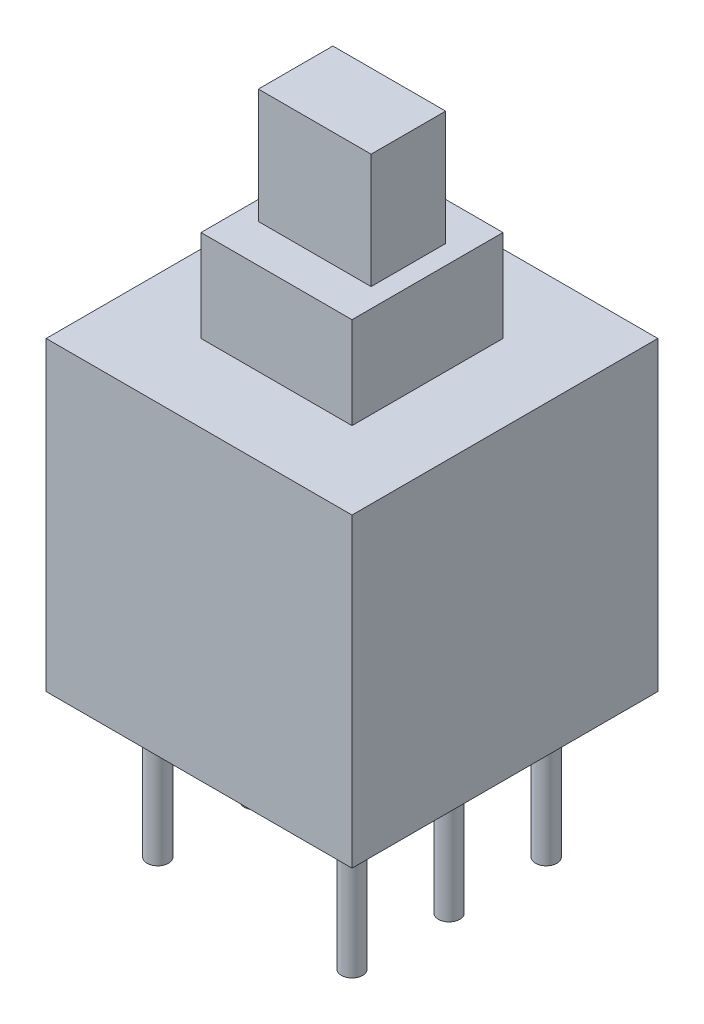
SolidWorks part; units mm, degrees
ref_plane "Front Plane" through (0, 0, 0) normal (0, 0, 1) x (1, 0, 0)
ref_plane "Top Plane" through (0, 0, 0) normal (0, 1, 0) x (1, 0, 0)
ref_plane "Right Plane" through (0, 0, 0) normal (1, 0, 0) x (0, 0, -1)
sketch "Sketch1" plane through (0, 0, 0) normal (0, 1, 0) x (1, 0, 0)
  line L1 (-4, -4) -> (4, -4)
  line L2 (-4, -4) -> (-4, 4)
  line L3 (-4, 4) -> (4, 4)
  line L4 (4, -4) -> (4, 4)
  line L5 (-4, -4) -> (4, 4) construction
  line L6 (-4, 4) -> (4, -4) construction
  point P0 (0, 0)
  dimension "D1" = 8
extrude "Boss-Extrude1" add sketch "Sketch1" along normal blind 8 contours L3 L4 L1 L2
sketch "Sketch2" plane through (0, 8, 0) normal (0, 1, 0) x (1, 0, 0)
  line L1 (-1.975, -1.975) -> (1.975, -1.975)
  line L2 (-1.975, -1.975) -> (-1.975, 1.975)
  line L3 (-1.975, 1.975) -> (1.975, 1.975)
  line L4 (1.975, -1.975) -> (1.975, 1.975)
  line L5 (-1.975, -1.975) -> (1.975, 1.975) construction
  line L6 (-1.975, 1.975) -> (1.975, -1.975) construction
  point P0 (0, 0)
  dimension "D1" = 3.95
extrude "Boss-Extrude2" add sketch "Sketch2" along normal blind 2.4 contours L3 L4 L1 L2
sketch "Sketch3" plane through (0, 10.4, 0) normal (0, 1, 0) x (1, 0, 0)
  line L1 (-1.475, -0.975) -> (1.475, -0.975)
  line L2 (-1.475, -0.975) -> (-1.475, 0.975)
  line L3 (-1.475, 0.975) -> (1.475, 0.975)
  line L4 (1.475, -0.975) -> (1.475, 0.975)
  line L5 (-1.475, -0.975) -> (1.475, 0.975) construction
  line L6 (-1.475, 0.975) -> (1.475, -0.975) construction
  point P0 (0, 0)
  dimension "D1" = 2.95
  dimension "D2" = 1.95
extrude "Boss-Extrude3" add sketch "Sketch3" along normal blind 3 contours L3 L4 L1 L2
sketch "Sketch4" plane through (0, 0, 0) normal (0, -1, 0) x (1, 0, 0)
  line L0 (2.54, 2.54) -> (2.54, 0) construction
  line L1 (2.54, 0) -> (2.54, -2.54) construction
  line L2 (-2.54, 0) -> (2.54, 0) construction
  line L3 (-2.54, -2.54) -> (-2.54, 0) construction
  line L4 (-2.54, 0) -> (-2.54, 2.54) construction
  circle A0 centre (2.54, 2.54) radius 0.28
  circle A1 centre (2.54, 0) radius 0.28
  circle A2 centre (2.54, -2.54) radius 0.28
  circle A3 centre (-2.54, -2.54) radius 0.28
  circle A4 centre (-2.54, 0) radius 0.28
  circle A5 centre (-2.54, 2.54) radius 0.28
  dimension "D3" = 0.56
  dimension "D1" = 2.54
  dimension "D2" = 5.08
extrude "Boss-Extrude4" add sketch "Sketch4" along normal blind 3.75 contours A0
